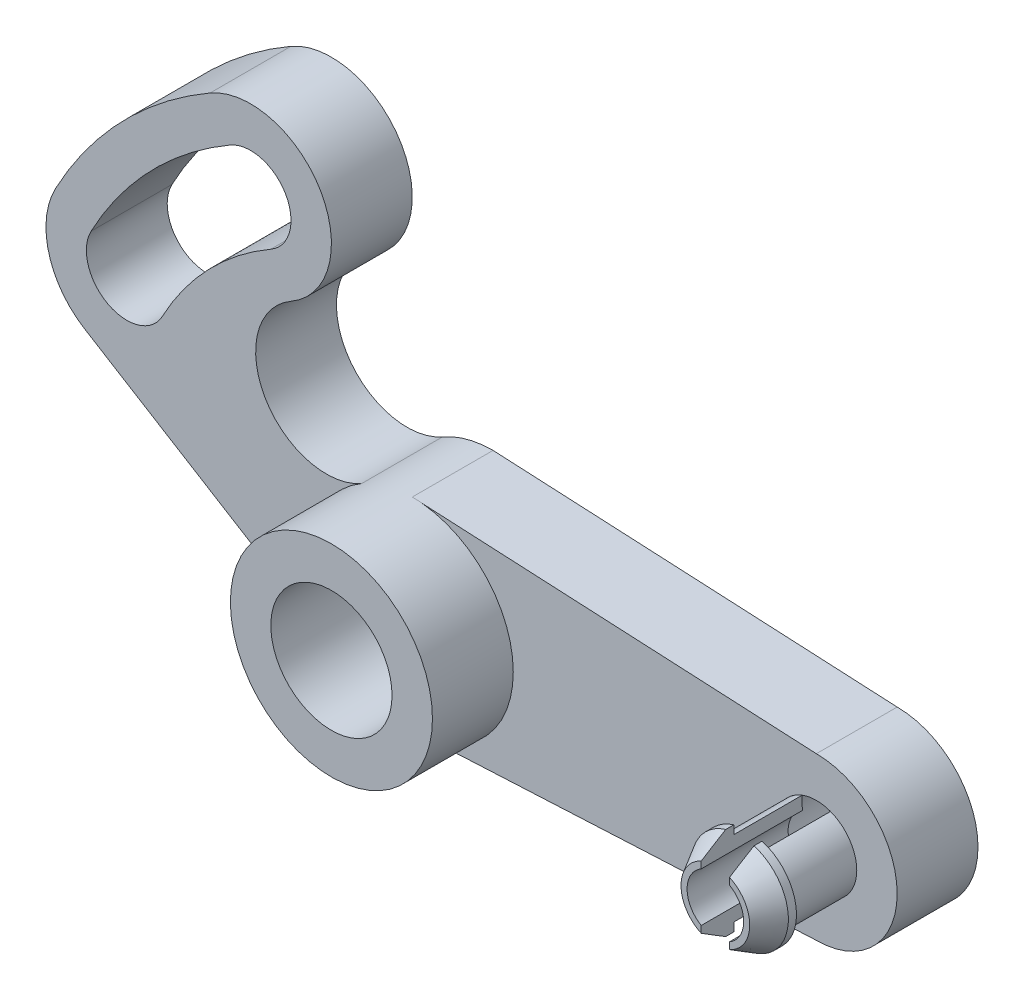
SolidWorks part; units mm, degrees
ref_plane "Plan de face" through (0, 0, 0) normal (0, 0, 1) x (1, 0, 0)
ref_plane "Plan de dessus" through (0, 0, 0) normal (0, 1, 0) x (1, 0, 0)
ref_plane "Plan de droite" through (0, 0, 0) normal (1, 0, 0) x (0, 0, -1)
sketch "Esquisse1" plane through (0, 0, 0) normal (0, 0, 1) x (1, 0, 0)
  line L0 (0, 0) -> (100, 0) construction
  line L1 (0, -25) -> (100, -20)
  line L2 (0, 25) -> (100, 20)
  line L3 (0, 0) -> (-206.3832, 0) construction
  line L4 (0, 0) -> (-204.179, 108.5639) construction
  line L5 (-79.4653, 42.2524) -> (-61.8063, 32.863) construction
  line L6 (0, 0) -> (-12.5, -21.6506) construction
  line L7 (-81.1085, 20.5189) -> (-12.5, -21.6506)
  line L8 (0, 0) -> (-7.5, 12.9904) construction
  line L9 (-45, 77.9423) -> (-35, 60.6218) construction
  line L10 (-35, 60.6218) -> (-74.2257, 128.5627) construction
  line L11 (-12.5, 21.6506) -> (-30, 51.9615) construction
  circle A0 centre (0, 0) radius 15
  arc A1 (0, 25) -> (-12.5, 21.6506) centre (0, 0) ccw
  arc A2 (100, -20) -> (100, 20) centre (100, 0) ccw
  circle A3 centre (100, 0) radius 10
  arc A4 (-70.6358, 37.5577) -> (-40, 69.282) centre (0, 0) cw construction
  arc A5 (-50, 86.6025) -> (-88.2948, 46.9472) centre (0, 0) ccw
  arc A6 (-70.6358, 37.5577) -> (-40, 69.282) centre (0, 0) cw construction
  arc A7 (-45, 77.9423) -> (-79.4653, 42.2524) centre (0, 0) ccw
  arc A8 (-35, 60.6218) -> (-61.8063, 32.863) centre (0, 0) ccw
  arc A9 (-35, 60.6218) -> (-45, 77.9423) centre (-40, 69.282) ccw
  arc A10 (-79.4653, 42.2524) -> (-61.8063, 32.863) centre (-70.6358, 37.5577) ccw
  arc A12 (-30, 51.9615) -> (-50, 86.6025) centre (-40, 69.282) ccw
  arc A13 (-88.2948, 46.9472) -> (-81.1085, 20.5189) centre (-70.6358, 37.5577) ccw
  arc A14 (-30, 51.9615) -> (-12.5, 21.6506) centre (-21.25, 36.8061) ccw
  arc A15 (-12.5, -21.6506) -> (0, -25) centre (0, 0) ccw
  point P12 (-57.5472, 55.5727)
  point P15 (-57.5472, 55.5727)
  dimension "D1" = 50
  dimension "D2" = 30
  dimension "D3" = 40
  dimension "D5" = 20
  dimension "D6" = 70
  dimension "D7" = 90
  dimension "D9" = 100
  dimension "D10" = 0
  dimension "D11" = 0
  dimension "D14" = 32
  dimension "D4" = 100
  dimension "D12" = 28
  dimension "D13" = 60
extrude "Boss.-Extru.1" add sketch "Esquisse1" along normal blind 20
sketch "Esquisse2" plane through (0, 0, 20) normal (0, 0, 1) x (1, 0, 0)
  circle A0 centre (0, 0) radius 15 construction
  circle A1 centre (0, 0) radius 15
  circle A2 centre (0, 0) radius 25
  dimension "D1" = 50
extrude "Boss.-Extru.2" add sketch "Esquisse2" along normal blind 20
chamfer "Chanfrein1" distance 2 angle 45 1 edges at (15, 0, 0)
ref_plane "Plan1" through (100, 0, 0) normal (1, 0, 0) x (0, 0, -1)
sketch "Esquisse5" plane through (100, 0, 0) normal (1, 0, 0) x (0, 0, -1)
  line L0 (0, 0) -> (-64.1916, 0) construction
  line L1 (-20, 0) -> (-20, 10) construction
  line L2 (-20, 24.8753) -> (-20, -24.8753) construction
  line L3 (-19.9879, 7) -> (-44.9879, 7)
  line L4 (-44.9879, 7) -> (-44.9879, 8.5)
  line L5 (-19.9879, 7) -> (-20, 10)
  line L6 (-36.9257, 12) -> (-36.9257, 10)
  line L7 (-36.9257, 10) -> (-20, 10)
  line L8 (-36.9257, 12) -> (-38.9257, 12)
  line L9 (-38.9257, 12) -> (-44.9879, 8.5)
  dimension "D1" = 25
  dimension "D2" = 2
  dimension "D3" = 2
  dimension "D4" = 3
  dimension "D5" = 1.5
  dimension "D6" = 30
revolve "Révolution3" add sketch "Esquisse5" angle 360 about L0
sketch "Esquisse6" plane through (0, 0, 44.9879) normal (0, 0, 1) x (1, 0, 0)
  line L1 (96.5, 12) -> (103.5, 12)
  line L2 (96.5, 12) -> (96.5, -12)
  line L3 (96.5, -12) -> (103.5, -12)
  line L4 (103.5, 12) -> (103.5, -12)
  line L5 (100, 0) -> (100, 21.109) construction
  line L6 (100, -24.7434) -> (100, 24.7434) construction
  point P5 (100, 12)
  dimension "D1" = 7
extrude "Enlèv. mat.-Extru.2" cut sketch "Esquisse6" against normal blind 25
